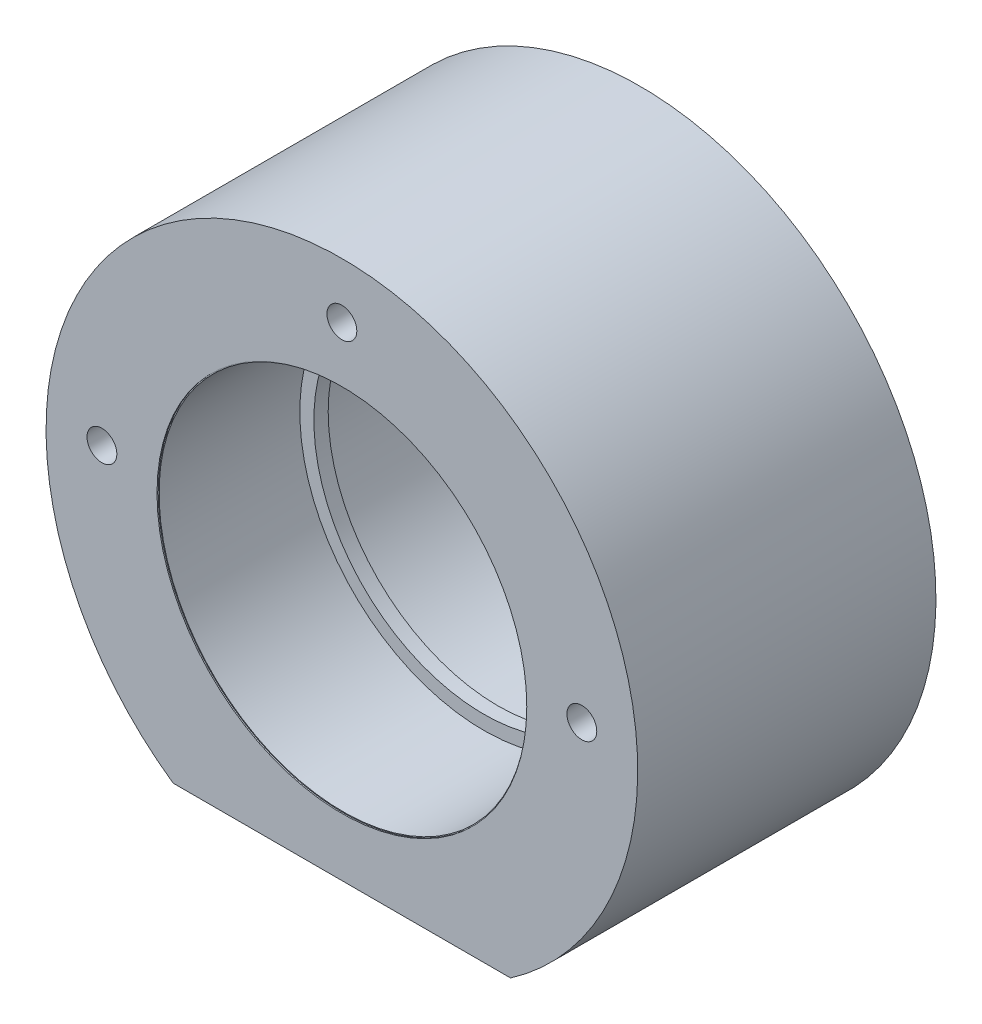
SolidWorks part; units mm, degrees
material "6061 Alloy"
ref_plane "Front Plane" through (0, 0, 0) normal (0, 0, 1) x (1, 0, 0)
ref_plane "Top Plane" through (0, 0, 0) normal (0, 1, 0) x (1, 0, 0)
ref_plane "Right Plane" through (0, 0, 0) normal (1, 0, 0) x (0, 0, -1)
sketch "Sketch1" plane through (0, 0, 0) normal (0, 0, 1) x (1, 0, 0)
  line L0 (-15.9687, 0) -> (15.9687, 0)
  arc A0 (15.9687, 0) -> (-15.9687, 0) centre (0, 23) ccw
  circle A1 centre (0, 23) radius 16.5
  dimension "D2" = 56
  dimension "D3" = 33
  dimension "D1" = 23
extrude "Boss-Extrude1" add sketch "Sketch1" along normal blind 50
sketch "Sketch2" plane through (0, 0, 50) normal (0, 0, 1) x (1, 0, 0)
  circle A0 centre (0, 23) radius 17.5
  arc A1 (15.9687, 0) -> (-15.9687, 0) centre (0, 23) ccw construction
  dimension "D1" = 35
extrude "Cut-Extrude1" cut sketch "Sketch2" against normal blind 11
ref_plane "Plane1" through (0, 0, 25) normal (0, 0, 1) x (1, 0, 0)
mirror "Mirror1" about plane through (0, 0, 25) normal (0, 0, 1) of "Cut-Extrude1"
sketch "Sketch3" plane through (0, 0, 0) normal (0, 0, -1) x (-1, 0, 0)
  circle A0 centre (0, 23) radius 16.5 construction
  circle A1 centre (0, 45.5) radius 2
  circle A2 centre (-22.5, 23) radius 2
  circle A3 centre (22.5, 23) radius 2
  point P0 (0, 23)
  dimension "D4" = 4
  dimension "D1" = 22.5
  dimension "D2" = 22.5
  dimension "D3" = 22.5
extrude "Cut-Extrude2" cut sketch "Sketch3" against normal blind 10
mirror "Mirror2" about plane through (0, 0, 25) normal (0, 0, 1) of "Cut-Extrude2"
scale "Scale1" scale about centroid uniform scaling yes scale factor 1.771429
sketch "Sketch4" plane through (0, 0, 49.8) normal (0, 0, 1) x (1, 0, 0)
  circle A0 centre (0, 21.6035) radius 28.4986
  circle A1 centre (0, 21.6035) radius 29.2286 construction
  circle A2 centre (0, 21.6035) radius 29.2286
  dimension "D1" = 0.73
extrude "Boss-Extrude2" add sketch "Sketch4" against normal up to surface (49.6 mm away) up to face at (-29.2286, 21.6035, 0.2)
ref_plane "Plane3" through (0, 0, 25) normal (0, 0, 1) x (1, 0, 0)
sketch "Sketch6" plane through (0, 0, 25) normal (0, 0, 1) x (1, 0, 0)
  line L0 (-28.2874, -19.1394) -> (28.2874, -19.1394) construction
  line L1 (-28.2874, -19.1394) -> (28.2874, -19.1394)
  circle A0 centre (0, 21.6035) radius 28.4986 construction
  circle A1 centre (0, 21.6035) radius 28.4986
  arc A2 (28.2874, -19.1394) -> (-28.2874, -19.1394) centre (0, 21.6035) ccw construction
  arc A3 (28.2874, -19.1394) -> (-28.2874, -19.1394) centre (0, 21.6035) ccw
extrude "Cut-Extrude6" cut sketch "Sketch6" along normal blind 19.285 from surface at -44.2857 starting at face at (-3.5429, 61.4606, -19.2857)
sketch "Sketch7" plane through (0, 0, 0) normal (0, 0, 1) x (1, 0, 0)
  line L1 (-28.2874, -19.1394) -> (28.2874, -19.1394)
  circle A1 centre (0, 21.6035) radius 28.4986
  arc A3 (28.2874, -19.1394) -> (-28.2874, -19.1394) centre (0, 21.6035) ccw
extrude "Cut-Extrude7" cut sketch "Sketch7" against normal blind 19.285 from surface at 69.2857 starting at face at (-3.5429, 61.4606, 69.2857)
sketch "Sketch9" plane through (0, 0, 50.0007) normal (0, 0, 1) x (1, 0, 0)
  circle A3 centre (0, 21.6035) radius 30.85
  dimension "D1" = 61.7
extrude "Cut-Extrude8" cut sketch "Sketch9" against normal blind 23.8
mirror "Mirror3" about plane through (0, 0, 25) normal (0, 0, 1) of "Cut-Extrude8"
sketch "Sketch10" plane through (0, 0, 50.0007) normal (0, 0, 1) x (1, 0, 0)
  circle A0 centre (0, 61.9035) radius 2.5
  circle A1 centre (-40.2334, 23.9194) radius 2.5
  circle A2 centre (40.2334, 23.9194) radius 2.5
  circle A3 centre (0, 21.6035) radius 40.3
  dimension "D1" = 5
  dimension "D2" = 5
  dimension "D3" = 5
  dimension "D4" = 80.6
extrude "Cut-Extrude9" cut sketch "Sketch10" against normal up to surface (50.0014 mm away) contours A0 A3 | A2 | A1
